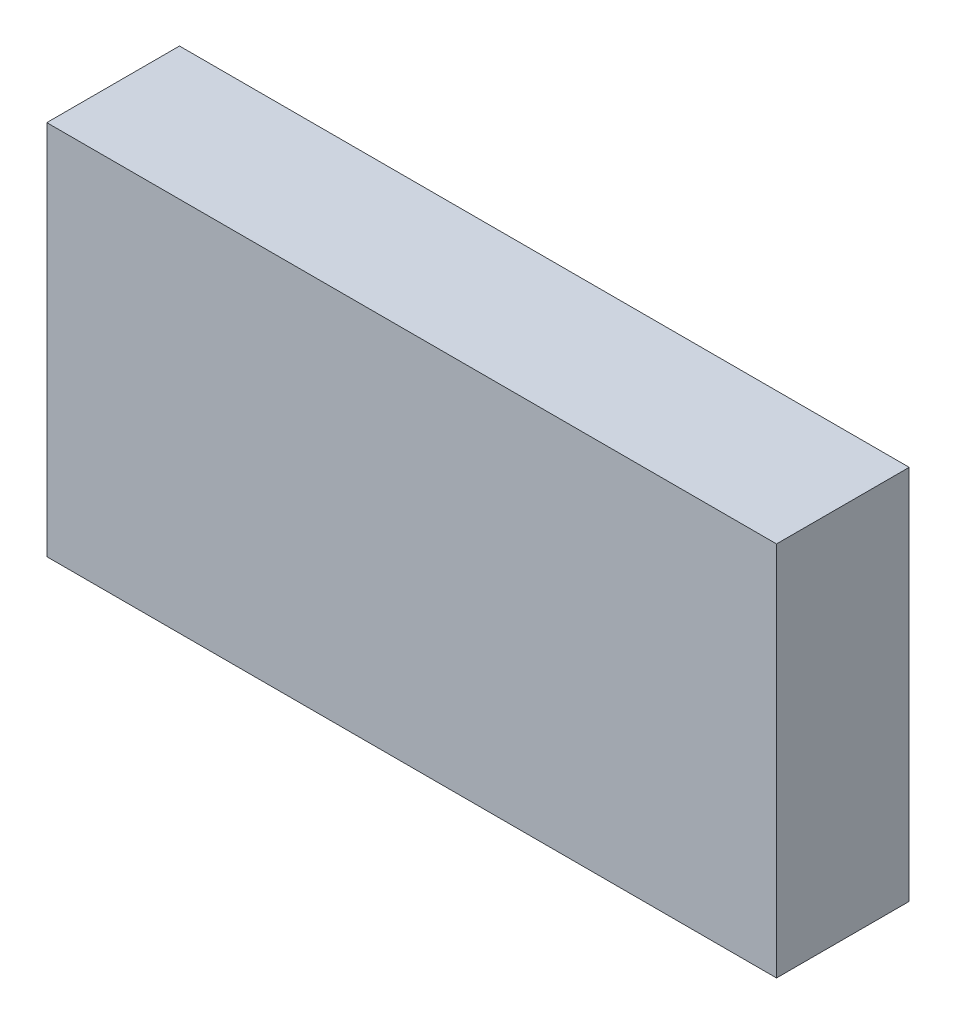
SolidWorks part; units mm, degrees
ref_plane "Front" through (0, 0, 0) normal (0, 0, 1) x (1, 0, 0)
ref_plane "Top" through (0, 0, 0) normal (0, 1, 0) x (1, 0, 0)
ref_plane "Right" through (0, 0, 0) normal (1, 0, 0) x (0, 0, -1)
sketch "Эскиз1" plane through (0, 0, 0) normal (0, 0, 1) x (1, 0, 0)
  line L1 (-0.6, -1) -> (0.6, -1)
  line L2 (-0.6, -1) -> (-0.6, 1)
  line L3 (-0.6, 1) -> (0.6, 1)
  line L4 (0.6, -1) -> (0.6, 1)
  line L5 (2.15, -1) -> (3.35, -1)
  line L6 (2.15, -1) -> (2.15, 1)
  line L7 (2.15, 1) -> (3.35, 1)
  line L8 (3.35, -1) -> (3.35, 1)
extrude "Pins of R4" [suppressed] add sketch "Эскиз1" along normal blind 0.02
ref_plane "Плоскость1" through (0, 0, 0.025) normal (0, 0, 1) x (1, 0, 0)
sketch "Эскиз2" plane through (0, 0, 0.025) normal (0, 0, 1) x (1, 0, 0)
  line L0 (-0.275, 0.85) -> (-0.275, -0.85)
  line L1 (3.025, 0.85) -> (3.025, -0.85)
  line L2 (-0.275, -0.85) -> (3.025, -0.85)
  line L3 (3.025, 0.85) -> (-0.275, 0.85)
  line L4 (-0.275, 0) -> (3.025, 0) construction
  line L5 (1.375, 0.85) -> (1.375, -0.85) construction
  dimension "D1" = 1.375
  dimension "D2" = 3.3
  dimension "D3" = 1.7
extrude "Вытянуть1" add sketch "Эскиз2" along normal blind 0.6
sketch "Эскиз5" plane through (0, 0.85, 0) normal (0, 1, 0) x (-1, 0, 0)
  line L0 (-3.025, 0.025) -> (0.275, 0.025) construction
  line L1 (-3.025, 0.625) -> (-2.3209, 0.625)
  line L2 (-3.025, 0.625) -> (-3.025, 0.025)
  line L3 (-3.025, 0.025) -> (-2.3209, 0.025)
  line L4 (-2.3209, 0.625) -> (-2.3209, 0.025)
  line L6 (0.275, 0.625) -> (-0.42, 0.625)
  line L7 (0.275, 0.625) -> (0.275, 0.025)
  line L8 (0.275, 0.025) -> (-0.42, 0.025)
  line L9 (-0.42, 0.625) -> (-0.42, 0.025)
extrude "Вырез-Вытянуть2" [suppressed] cut sketch "Эскиз5" against normal blind 0.01
sketch "Эскиз6" plane through (0, -0.85, 0) normal (0, -1, 0) x (1, 0, 0)
  line L0 (-0.275, 0.025) -> (3.025, 0.025) construction
  line L1 (3.025, 0.625) -> (2.3226, 0.625)
  line L2 (3.025, 0.625) -> (3.025, 0.025)
  line L3 (3.025, 0.025) -> (2.3226, 0.025)
  line L4 (2.3226, 0.625) -> (2.3226, 0.025)
  line L6 (-0.275, 0.625) -> (0.4209, 0.625)
  line L7 (-0.275, 0.625) -> (-0.275, 0.025)
  line L8 (-0.275, 0.025) -> (0.4209, 0.025)
  line L9 (0.4209, 0.625) -> (0.4209, 0.025)
extrude "Вырез-Вытянуть3" [suppressed] cut sketch "Эскиз6" against normal blind 0.01
